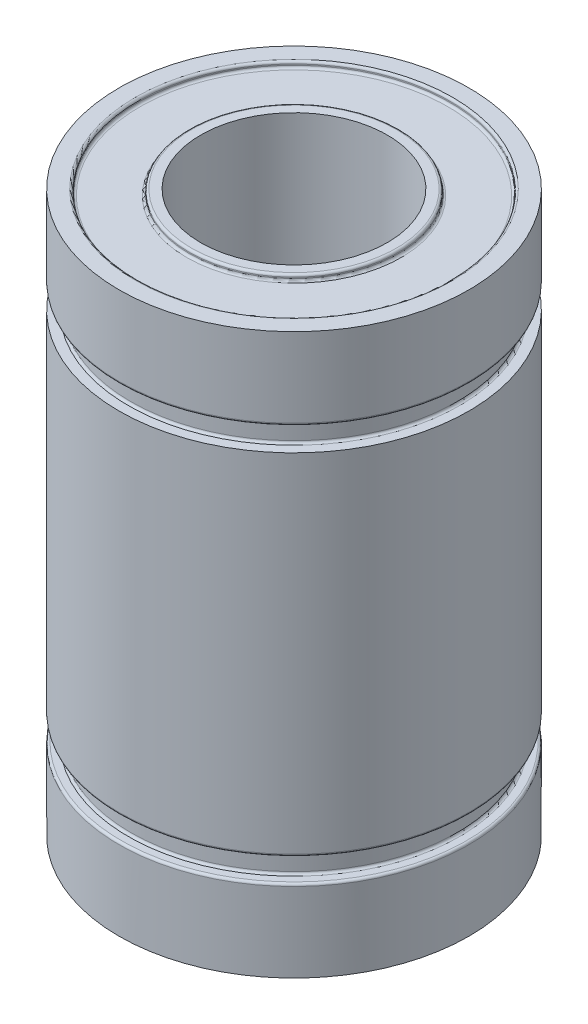
SolidWorks part; units mm, degrees
ref_plane "Front Plane" through (0, 0, 0) normal (0, 0, 1) x (1, 0, 0)
ref_plane "Top Plane" through (0, 0, 0) normal (0, 1, 0) x (1, 0, 0)
ref_plane "Right Plane" through (0, 0, 0) normal (1, 0, 0) x (0, 0, -1)
sketch "Sketch1" plane through (0, 0, 0) normal (0, 1, 0) x (1, 0, 0)
  circle A0 centre (0, 0) radius 7.5
  circle A1 centre (0, 0) radius 4
  dimension "D1" = 15
  dimension "D2" = 8
extrude "Boss-Extrude1" add sketch "Sketch1" along normal mid plane 24
sketch "Sketch2" plane through (0, 0, 0) normal (0, 0, 1) x (1, 0, 0)
  line L0 (-7.5, 12) -> (-7.5, -12) construction
  line L1 (-7.5, 8.5) -> (-7, 8.5)
  line L2 (-7.5, 8.5) -> (-7.5, 7.5)
  line L3 (-7.5, 7.5) -> (-7, 7.5)
  line L4 (-7, 8.5) -> (-7, 7.5)
  line L5 (7.5, 12) -> (-7.5, 12) construction
  line L6 (0, 12) -> (0, 0) construction
  line L7 (0, 0) -> (7.5, 0) construction
  line L8 (7.5, -12) -> (7.5, 12) construction
  line L9 (-7, -8.5) -> (-7, -7.5)
  line L10 (-7.5, -7.5) -> (-7, -7.5)
  line L11 (-7.5, -8.5) -> (-7.5, -7.5)
  line L12 (-7.5, -8.5) -> (-7, -8.5)
  dimension "D1" = 0.5
  dimension "D2" = 3.5
  dimension "D3" = 1
revolve "Cut-Revolve2" cut sketch "Sketch2" angle 360 about L6
sketch "Sketch3" plane through (0, -12, 0) normal (0, -1, 0) x (1, 0, 0)
  circle A0 centre (0, 0) radius 6.7
  circle A1 centre (0, 0) radius 7.5 construction
  circle A2 centre (0, 0) radius 4.5
  circle A3 centre (0, 0) radius 4 construction
  dimension "D1" = 0.8
  dimension "D2" = 0.5
extrude "Cut-Extrude1" cut sketch "Sketch3" against normal blind 0.25
mirror "Mirror1" about plane through (0, 0, 0) normal (0, 1, 0) of "Cut-Extrude1"
fillet "Fillet1" radius 0.1 15 edges at (0, 7.5, 7) (0, 12, -4.5) (0, 11.75, -4.5) (0, 11.75, -6.7) (0, 12, -6.7) (0, 8.5, 7.5) (0, 8.5, 7) (0, -12, -6.7) (0, -11.75, -6.7) (0, -11.75, -4.5) (0, -12, -4.5) (0, -7.5, 7.5) (0, -7.5, 7) (0, -8.5, 7.5) (0, -8.5, 7)
